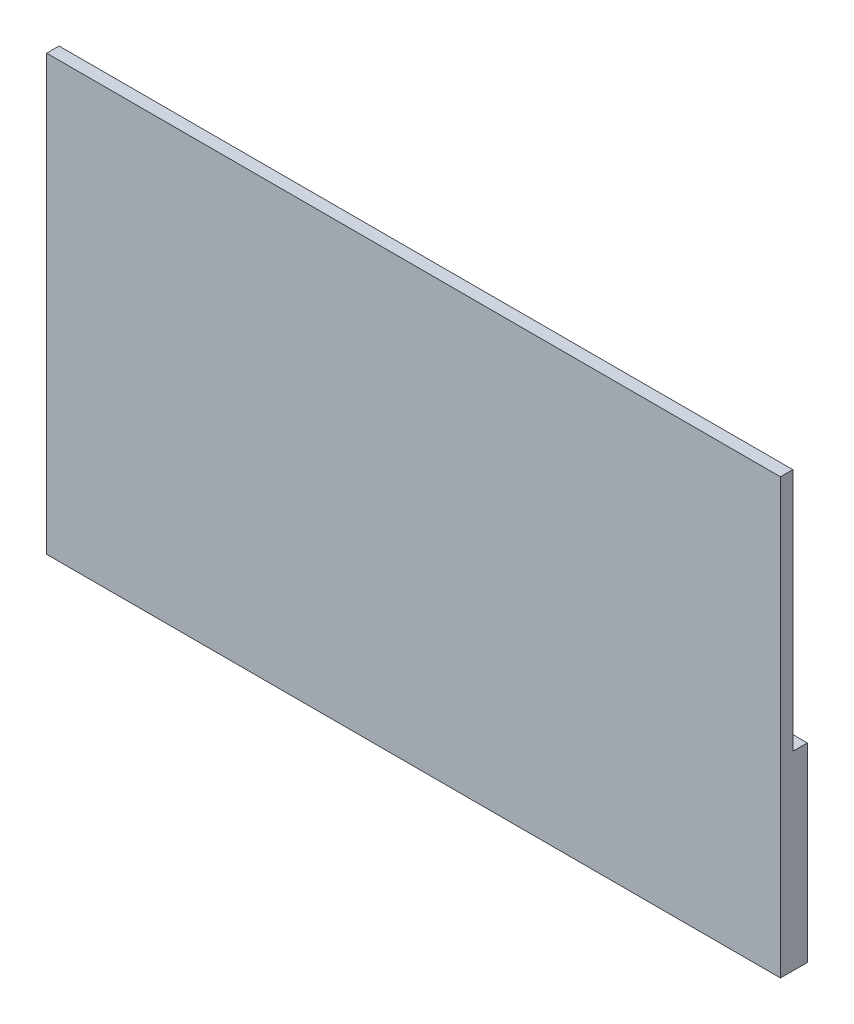
SolidWorks part; units mm, degrees
ref_plane "Front Plane" through (0, 0, 0) normal (0, 0, 1) x (1, 0, 0)
ref_plane "Top Plane" through (0, 0, 0) normal (0, 1, 0) x (1, 0, 0)
ref_plane "Right Plane" through (0, 0, 0) normal (1, 0, 0) x (0, 0, -1)
sketch "Sketch1" plane through (0, 0, 0) normal (0, 0, 1) x (1, 0, 0)
  line L1 (-177.5, -105) -> (177.5, -105)
  line L2 (-177.5, -105) -> (-177.5, 105)
  line L3 (-177.5, 105) -> (177.5, 105)
  line L4 (177.5, -105) -> (177.5, 105)
  line L5 (-177.5, -105) -> (177.5, 105) construction
  line L6 (-177.5, 105) -> (177.5, -105) construction
  point P0 (0, 0)
  dimension "D1" = 355
  dimension "D2" = 210
extrude "Boss-Extrude1" add sketch "Sketch1" along normal blind 6
sketch "Sketch2" plane through (0, 0, 0) normal (0, 0, 1) x (1, 0, 0)
  line L1 (-177.5, -105) -> (177.5, -105)
  line L2 (-177.5, -105) -> (-177.5, -13)
  line L3 (-177.5, -13) -> (177.5, -13)
  line L4 (177.5, -105) -> (177.5, -13)
  point P5 (177.5, 0)
  point P6 (177.5, -105)
  dimension "D1" = 92
extrude "Boss-Extrude2" add sketch "Sketch2" against normal blind 7
sketch "Sketch3" plane through (0, 0, -7) normal (0, 0, -1) x (-1, 0, 0)
  line L0 (0, 0) -> (0, -105) construction
  line L1 (177.5, -105) -> (-177.5, -105) construction
  line L2 (-37.5, -29) -> (37.5, -29) construction
  line L3 (-177.5, -13) -> (177.5, -13) construction
  point P5 (-37.5, -29)
  point P6 (37.5, -29)
  point P7 (0, -29)
  dimension "D1" = 16
  dimension "D2" = 75
hole_wizard "M4 Tapped Hole2" positions "Sketch3" profile "Sketch4" tap size "M4" standard "DIN"
sketch "Sketch4" plane through (-37.5, -29, -7) normal (1, 0, 0) x (0, 1, 0)
  line L0 (0, 0) -> (0, 3)
  line L1 (0, 3) -> (1.65, 2.0086)
  line L2 (1.65, 2.0086) -> (1.65, 0.375)
  line L3 (1.65, 0.375) -> (2.025, 0)
  line L5 (2.025, 0) -> (0, 0)
  line L6 (-1.65, 0.375) -> (-2.025, 0) construction
  line L10 (0, 3) -> (-1.65, 2.0086) construction
  line L11 (0, -6.35) -> (0, 107.95) construction
  dimension "Tap Drill Dia." = 3.3
  dimension "Tap Drill Depth" = 3
  dimension "Near C'Sink Dia." = 4.05
  dimension "Near C'Sink Angle" = 90
  dimension "Drill Angle" = 118
cosmetic thread "Hole Thread1" parameters "D1"=8, "D2"=4
cosmetic thread "Hole Thread2" parameters "D1"=8, "D2"=4
